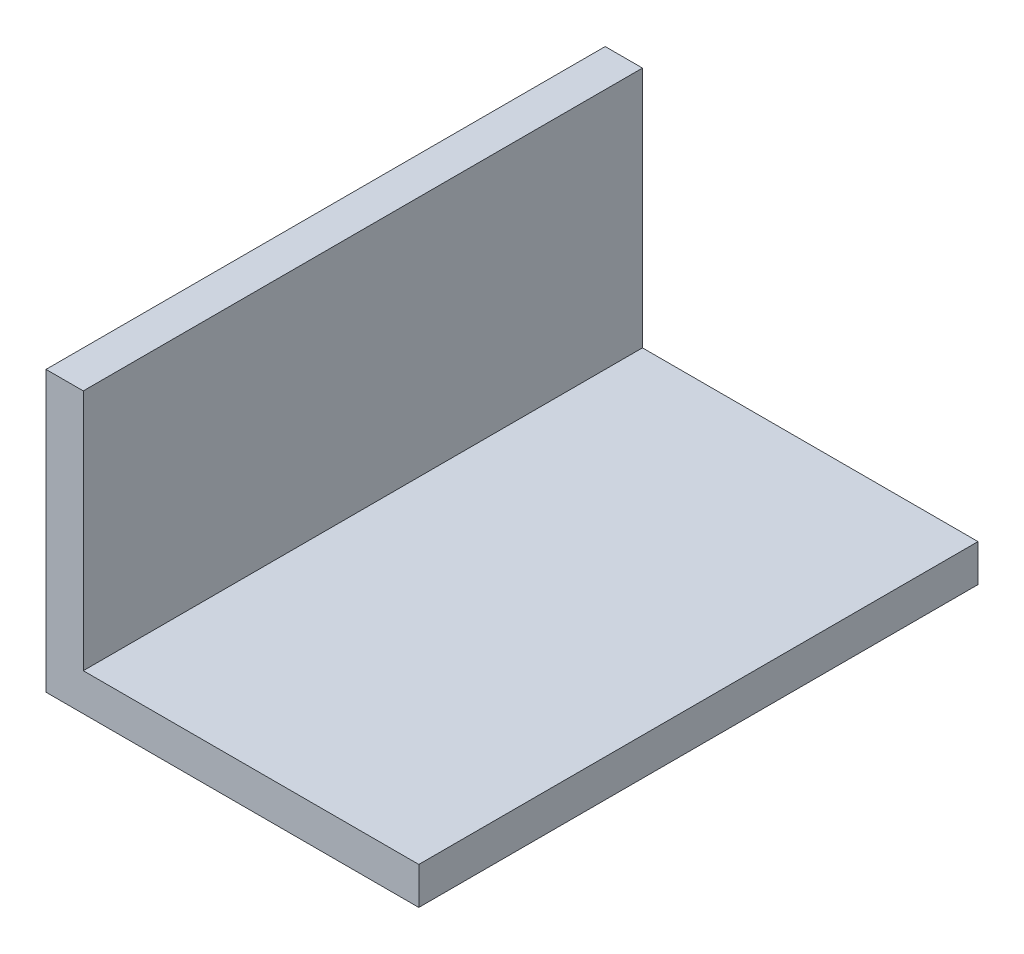
SolidWorks part; units mm, degrees
ref_plane "前视基准面" through (0, 0, 0) normal (0, 0, 1) x (1, 0, 0)
ref_plane "上视基准面" through (0, 0, 0) normal (0, 1, 0) x (1, 0, 0)
ref_plane "右视基准面" through (0, 0, 0) normal (1, 0, 0) x (0, 0, -1)
ref_plane "基准面1" through (40, 0, 0) normal (1, 0, 0) x (0, 0, -1)
sketch "草图1" plane through (40, 0, 0) normal (1, 0, 0) x (0, 0, -1)
  line L0 (-50, -3) -> (-20, -3)
  line L1 (-20, -3) -> (-20, 12)
  line L2 (-20, 12) -> (-50, 12)
  line L3 (-50, 12) -> (-50, -3)
extrude "凸台-拉伸1" add sketch "草图1" against normal blind 20
sketch "草图2" plane through (0, 0, 50) normal (0, 0, 1) x (1, 0, 0)
  line L1 (40, 12) -> (22, 12)
  line L2 (40, 12) -> (40, -1)
  line L3 (40, -1) -> (22, -1)
  line L4 (22, 12) -> (22, -1)
  dimension "D1" = 13
extrude "切除-拉伸1" cut sketch "草图2" against normal through all
scale "缩放比例1" scale about origin uniform scaling yes scale factor 1.7
